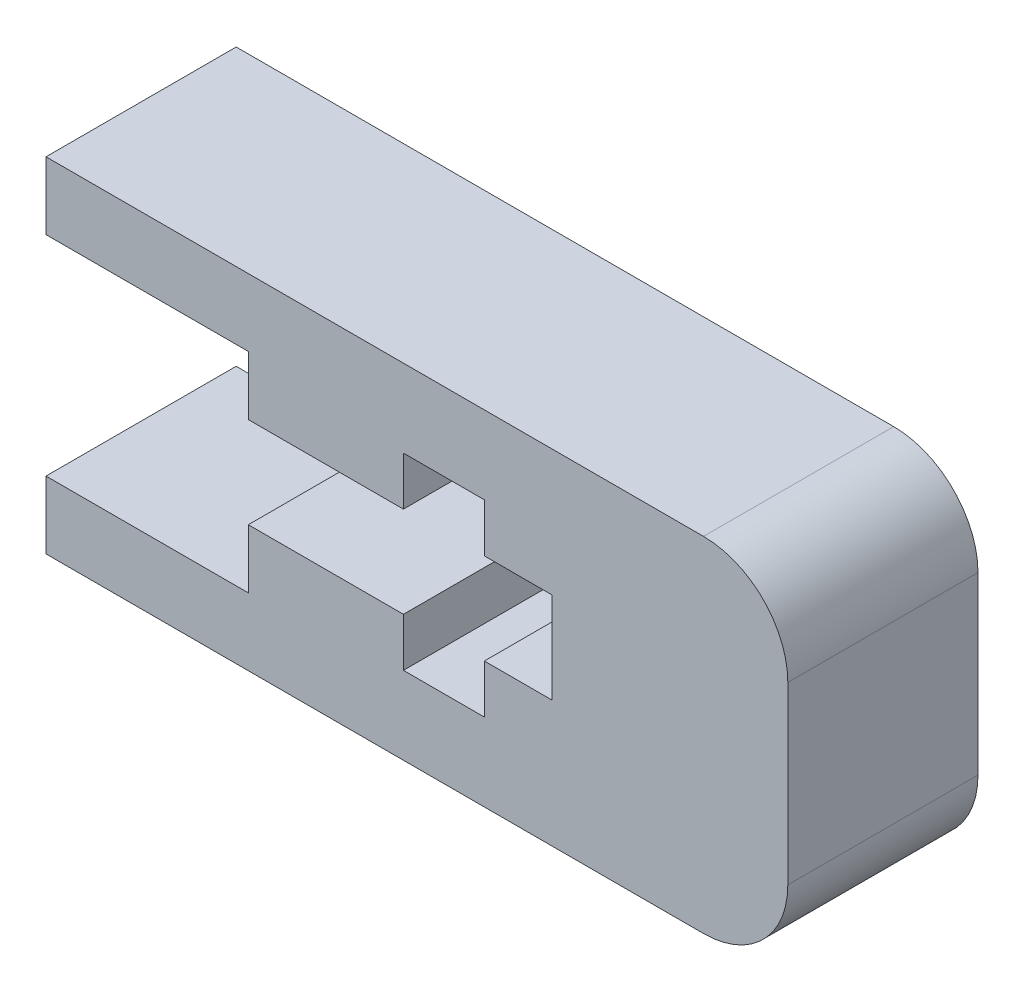
SolidWorks part; units mm, degrees
material "Acrylic (Medium-high impact)"
ref_plane "Front Plane" through (0, 0, 0) normal (0, 0, 1) x (1, 0, 0)
ref_plane "Top Plane" through (0, 0, 0) normal (0, 1, 0) x (1, 0, 0)
ref_plane "Right Plane" through (0, 0, 0) normal (1, 0, 0) x (0, 0, -1)
sketch "Sketch1" plane through (0, 0, 0) normal (0, 0, 1) x (1, 0, 0)
  line L0 (727.3394, 350.7563) -> (749.3394, 350.7563)
  line L2 (742.3394, 347.0063) -> (742.3394, 344.3063)
  line L3 (727.3394, 348.7563) -> (733.3394, 348.7563)
  line L4 (733.3394, 348.7563) -> (733.3394, 347.0063)
  line L5 (733.3394, 347.0063) -> (737.9394, 347.0063)
  line L6 (737.9394, 348.4463) -> (740.3394, 348.4463)
  line L7 (-245.8122, 345.6563) -> (49754.1878, 345.6563) construction
  line L8 (727.3394, 340.5563) -> (727.3394, 342.5563)
  line L9 (737.9394, 344.3063) -> (737.9394, 342.8663)
  line L10 (740.3394, 342.8663) -> (740.3394, 344.3063)
  line L11 (740.3394, 344.3063) -> (742.3394, 344.3063)
  line L12 (737.9394, 342.8663) -> (740.3394, 342.8663)
  line L13 (733.3394, 344.3063) -> (737.9394, 344.3063)
  line L14 (740.3394, 347.0063) -> (742.3394, 347.0063)
  line L15 (740.3394, 348.4463) -> (740.3394, 347.0063)
  line L16 (733.3394, 342.5563) -> (733.3394, 344.3063)
  line L17 (737.9394, 347.0063) -> (737.9394, 348.4463)
  line L18 (727.3394, 342.5563) -> (733.3394, 342.5563)
  line L19 (727.3394, 340.5563) -> (749.3394, 340.5563)
  line L20 (749.3394, 350.7563) -> (749.3394, 340.5563)
  line L34 (727.3394, 350.7563) -> (727.3394, 348.7563)
  point P7 (738.3394, 350.7563)
  point P24 (742.3394, 345.6563)
  point P28 (738.3394, 340.5563)
  point P46 (738.3394, 350.7563)
  dimension "D1" = 2
  dimension "D2" = 4.6
  dimension "D3" = 6
  dimension "D4" = 1.44
  dimension "D5" = 2.4
  dimension "D6" = 2
  dimension "D7" = 1.75
  dimension "D8" = 16
  dimension "D9" = 2.7
extrude "Boss-Extrude2" add sketch "Sketch1" along normal blind 5.64
fillet "Fillet1" radius 2.5 2 edges at (749.3394, 340.5563, 2.82) (749.3394, 350.7563, 2.82)
